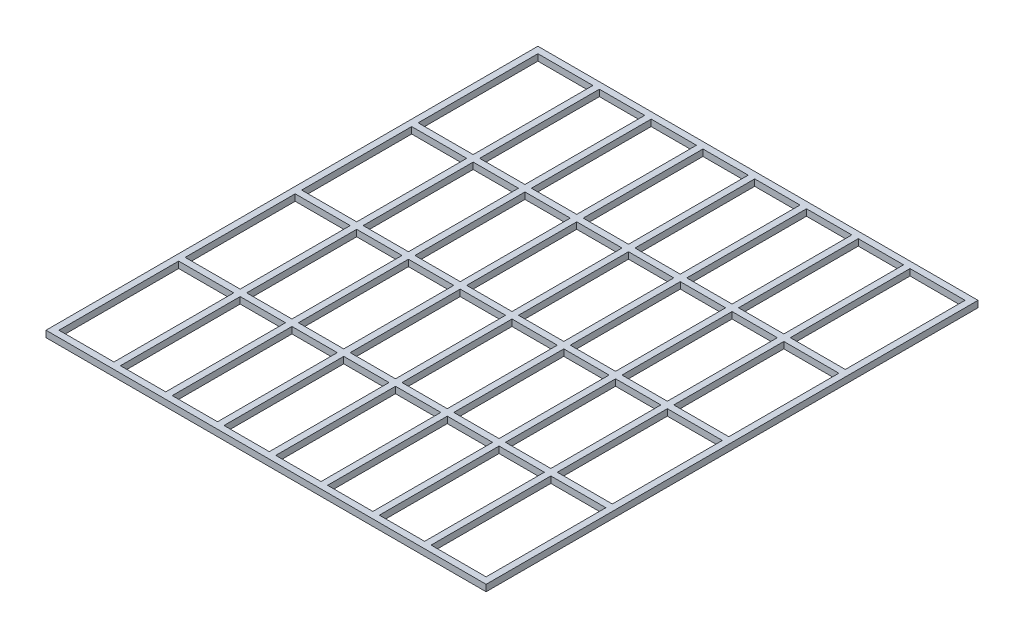
SolidWorks part; units mm, degrees
ref_plane "Front" through (0, 0, 0) normal (0, 0, 1) x (1, 0, 0)
ref_plane "Top" through (0, 0, 0) normal (0, 1, 0) x (1, 0, 0)
ref_plane "Right" through (0, 0, 0) normal (1, 0, 0) x (0, 0, -1)
sketch "Sketch1" plane through (0, 0, 0) normal (0, 1, 0) x (1, 0, 0)
  line L0 (-1257.3, 1409.7) -> (1257.3, 1409.7)
  line L1 (-1295.4, 1447.8) -> (1295.4, 1447.8)
  line L2 (-1295.4, 1447.8) -> (-1295.4, -1447.8)
  line L3 (-1295.4, -1447.8) -> (1295.4, -1447.8)
  line L4 (1295.4, 1447.8) -> (1295.4, -1447.8)
  line L5 (-1295.4, 1447.8) -> (1295.4, -1447.8) construction
  line L6 (-1295.4, -1447.8) -> (1295.4, 1447.8) construction
  line L7 (1257.3, 1409.7) -> (1257.3, -1409.7)
  line L8 (-1257.3, -1409.7) -> (1257.3, -1409.7)
  line L9 (-1257.3, 1409.7) -> (-1257.3, -1409.7)
  point P0 (0, 0)
  dimension "D1" = 2895.6
  dimension "D2" = 2590.8
  dimension "D3" = 38.1
extrude "Boss-Extrude1" add sketch "Sketch1" along normal blind 38.1
sketch "Sketch2" plane through (0, 38.1, 0) normal (0, 1, 0) x (1, 0, 0)
  line L0 (-1295.4, -1447.8) -> (1295.4, -1447.8) construction
  line L1 (-19.05, 1447.8) -> (19.05, 1447.8)
  line L2 (-19.05, 1447.8) -> (-19.05, -1447.8)
  line L3 (-19.05, -1447.8) -> (19.05, -1447.8)
  line L4 (19.05, 1447.8) -> (19.05, -1447.8)
  line L5 (-19.05, 1447.8) -> (19.05, -1447.8) construction
  line L6 (-19.05, -1447.8) -> (19.05, 1447.8) construction
  point P0 (0, 0)
  dimension "D1" = 38.1
extrude "Boss-Extrude2" add sketch "Sketch2" against normal up to surface (38.1 mm away) up to face at (0, 0, 0)
pattern_linear "LPattern1" count 4 spacing 304.8 along (-1, 0, 0) of "Boss-Extrude2"
pattern_linear "LPattern2" count 4 spacing 304.8 along (1, 0, 0) of "Boss-Extrude2"
sketch "Sketch3" plane through (0, 38.1, 0) normal (0, 1, 0) x (1, 0, 0)
  line L0 (-1295.4, 1447.8) -> (-1295.4, -1447.8) construction
  line L1 (1295.4, 19.05) -> (-1295.4, 19.05)
  line L2 (1295.4, 19.05) -> (1295.4, -19.05)
  line L3 (1295.4, -19.05) -> (-1295.4, -19.05)
  line L4 (-1295.4, 19.05) -> (-1295.4, -19.05)
  line L5 (1295.4, 19.05) -> (-1295.4, -19.05) construction
  line L6 (1295.4, -19.05) -> (-1295.4, 19.05) construction
  point P0 (0, 0)
  dimension "D1" = 38.1
extrude "Boss-Extrude3" add sketch "Sketch3" against normal up to surface (38.1 mm away) up to face at (1095.375, 0, 0)
pattern_linear "LPattern3" count 2 spacing 685.8 along (0, 0, 1) of "Boss-Extrude3"
pattern_linear "LPattern4" count 2 spacing 685.8 along (0, 0, -1) of "Boss-Extrude3"
